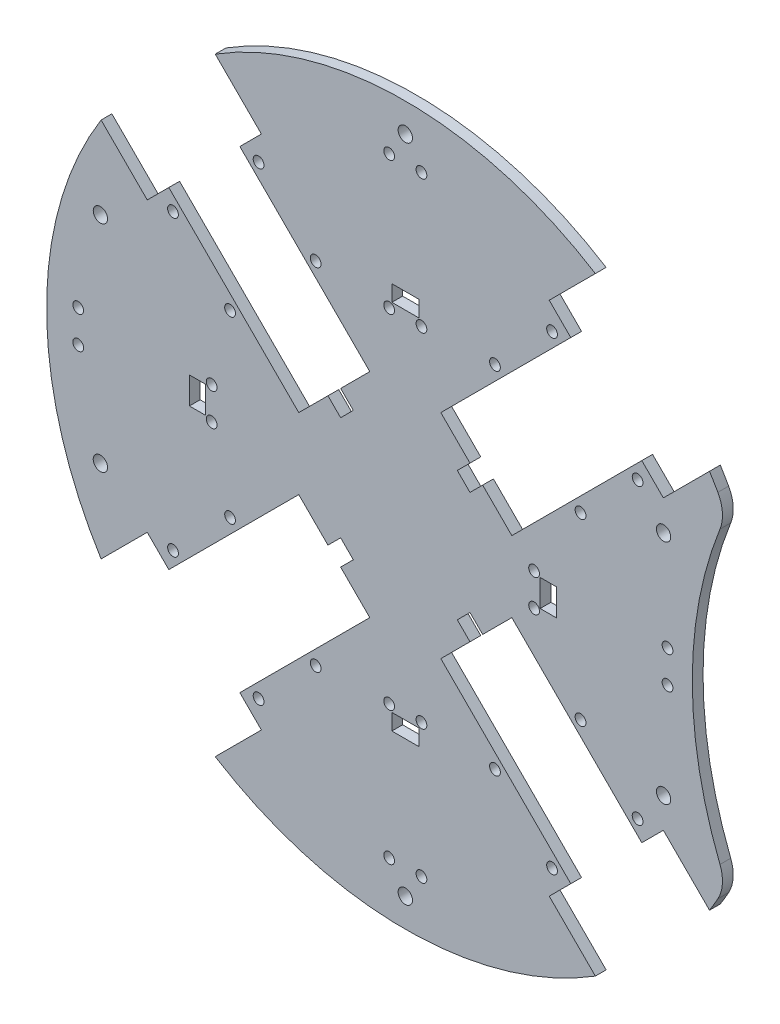
SolidWorks part; units mm, degrees
ref_plane "Alzado" through (0, 0, 0) normal (0, 0, 1) x (1, 0, 0)
ref_plane "Planta" through (0, 0, 0) normal (0, 1, 0) x (1, 0, 0)
ref_plane "Vista lateral" through (0, 0, 0) normal (1, 0, 0) x (0, 0, -1)
sketch "Croquis1" plane through (0, 0, 0) normal (0, 0, 1) x (1, 0, 0)
  circle A0 centre (0, 0) radius 100
  dimension "D1" = 200
extrude "Saliente-Extruir1" add sketch "Croquis1" along normal blind 3
sketch "Croquis3" plane through (0, 0, 3) normal (0, 0, 1) x (1, 0, 0)
  line L0 (0, 0) -> (190, 0) construction
  circle A0 centre (190, 0) radius 110
  dimension "D1" = 220
  dimension "D2" = 190
extrude "Cortar-Extruir1" cut sketch "Croquis3" against normal blind 3
fillet "Redondeo1" radius 10 2 edges at (89.4737, -44.6594, 1.5) (89.4737, 44.6594, 1.5)
sketch "Croquis5" plane through (0, 0, 3) normal (0, 0, 1) x (1, 0, 0)
  line L0 (0, -100) -> (0, 100) construction
  line L1 (-100, 0) -> (80, 0) construction
  line L2 (0, 0) -> (-70.7107, -70.7107) construction
  line L3 (-70.7107, -70.7107) -> (70.7107, 70.7107) construction
  line L4 (0, 0) -> (-70.7107, 70.7107) construction
  line L5 (-70.7107, 70.7107) -> (70.7107, -70.7107) construction
  line L6 (-29.6985, -9.8995) -> (-9.8995, -29.6985)
  line L7 (-29.6985, -9.8995) -> (-84.1457, -64.3467)
  line L8 (-9.8995, -29.6985) -> (-64.3467, -84.1457)
  line L9 (-84.1457, -64.3467) -> (-64.3467, -84.1457)
  line L10 (-9.8995, 29.6985) -> (-29.6985, 9.8995)
  line L11 (-9.8995, 29.6985) -> (-64.3467, 84.1457)
  line L12 (-64.3467, 84.1457) -> (-84.1457, 64.3467)
  line L13 (-29.6985, 9.8995) -> (-84.1457, 64.3467)
  line L14 (29.6985, 9.8995) -> (9.8995, 29.6985)
  line L15 (29.6985, 9.8995) -> (84.1457, 64.3467)
  line L16 (84.1457, 64.3467) -> (64.3467, 84.1457)
  line L17 (9.8995, 29.6985) -> (64.3467, 84.1457)
  line L18 (9.8995, -29.6985) -> (29.6985, -9.8995)
  line L19 (9.8995, -29.6985) -> (64.3467, -84.1457)
  line L20 (64.3467, -84.1457) -> (84.1457, -64.3467)
  line L21 (29.6985, -9.8995) -> (84.1457, -64.3467)
  arc A0 (87.1345, 49.0671) -> (87.1345, -49.0671) centre (0, 0) ccw construction
  arc A1 (87.7193, 40.4803) -> (87.7193, -40.4803) centre (190, 0) ccw construction
  point P36 (0, 0)
  dimension "D1" = 45
  dimension "D2" = 45
  dimension "D3" = 28
  dimension "D4" = 14
  dimension "D5" = 5
  dimension "D6" = 77
  dimension "D8" = 5
  dimension "D9" = 5
  dimension "D7" = 4
extrude "Cortar-Extruir2" cut sketch "Croquis5" against normal blind 10
sketch "Croquis7" plane through (0, 0, 3) normal (0, 0, 1) x (1, 0, 0)
  line L0 (-71.9393, -40.1195) -> (-40.1195, -71.9393)
  line L1 (-71.9393, -40.1195) -> (-88.9099, -57.0901)
  line L2 (-40.1195, -71.9393) -> (-57.0901, -88.9099)
  line L3 (-88.9099, -57.0901) -> (-57.0901, -88.9099)
  line L4 (-29.6985, -9.8995) -> (-79.9138, -60.1148) construction
  line L7 (-73, -73) -> (0, 0) construction
  line L8 (-40.1195, 71.9393) -> (-71.9393, 40.1195)
  line L9 (-40.1195, 71.9393) -> (-57.0901, 88.9099)
  line L10 (-57.0901, 88.9099) -> (-88.9099, 57.0901)
  line L11 (-71.9393, 40.1195) -> (-88.9099, 57.0901)
  line L12 (71.9393, 40.1195) -> (40.1195, 71.9393)
  line L13 (71.9393, 40.1195) -> (88.9099, 57.0901)
  line L14 (88.9099, 57.0901) -> (57.0901, 88.9099)
  line L15 (40.1195, 71.9393) -> (57.0901, 88.9099)
  line L16 (40.1195, -71.9393) -> (71.9393, -40.1195)
  line L17 (40.1195, -71.9393) -> (57.0901, -88.9099)
  line L18 (57.0901, -88.9099) -> (88.9099, -57.0901)
  line L19 (71.9393, -40.1195) -> (88.9099, -57.0901)
  line L23 (-21.5668, -18.0312) -> (-18.0312, -21.5668)
  line L24 (-21.5668, -18.0312) -> (-18.0312, -14.4957)
  line L25 (-18.0312, -21.5668) -> (-14.4957, -18.0312)
  line L26 (-18.0312, -14.4957) -> (-14.4957, -18.0312)
  line L42 (-21.5668, 18.0312) -> (-18.0312, 14.4957)
  line L43 (-18.0312, 21.5668) -> (-14.4957, 18.0312)
  line L44 (-18.0312, 21.5668) -> (-21.5668, 18.0312)
  line L45 (-14.4957, 18.0312) -> (-18.0312, 14.4957)
  line L46 (18.0312, 21.5668) -> (14.4957, 18.0312)
  line L47 (21.5668, 18.0312) -> (18.0312, 14.4957)
  line L48 (21.5668, 18.0312) -> (18.0312, 21.5668)
  line L49 (18.0312, 14.4957) -> (14.4957, 18.0312)
  line L50 (21.5668, -18.0312) -> (18.0312, -14.4957)
  line L51 (18.0312, -21.5668) -> (14.4957, -18.0312)
  line L52 (18.0312, -21.5668) -> (21.5668, -18.0312)
  line L53 (14.4957, -18.0312) -> (18.0312, -14.4957)
  arc A0 (-79.9138, 60.1148) -> (-79.9138, -60.1148) centre (0, 0) ccw construction
  arc A2 (-79.9138, 60.1148) -> (-79.9138, -60.1148) centre (0, 0) ccw construction
  point P24 (0, 0)
  point P47 (0, -3.5355)
  point P48 (0, 0)
  dimension "D1" = 90
  dimension "D2" = 45
  dimension "D3" = 24
  dimension "D4" = 73
  dimension "D5" = 360
  dimension "D6" = 4
  dimension "D7" = 79.2376
  dimension "D8" = 22.5
  dimension "D9" = 5
  dimension "D10" = 2.5
  dimension "D11" = 5
  dimension "D12" = 23
  dimension "D14" = 23
  dimension "D15" = 23
  dimension "D13" = 4
extrude "Cortar-Extruir3" cut sketch "Croquis7" against normal blind 10
sketch "Croquis8" plane through (0, 0, 3) normal (0, 0, 1) x (1, 0, 0)
  line L0 (-71.9393, 40.1195) -> (-65.9289, 46.1299) construction
  line L1 (-65.9289, 46.1299) -> (-29.6985, 9.8995) construction
  line L2 (0, 0) -> (0, 100) construction
  line L3 (-46.1299, 65.9289) -> (-40.1195, 71.9393) construction
  line L4 (52.9877, 84.8075) -> (40.1195, 71.9393) construction
  line L7 (-65.9289, -46.1299) -> (-71.9393, -40.1195) construction
  line L8 (-29.6985, -9.8995) -> (-65.9289, -46.1299) construction
  line L9 (-52.9877, -84.8075) -> (-40.1195, -71.9393) construction
  line L11 (-100, 0) -> (80, 0) construction
  line L14 (71.9393, 40.1195) -> (84.8075, 52.9877) construction
  circle A0 centre (-64.7622, 40.9044) radius 1.5
  circle A1 centre (-48.8523, 24.9945) radius 1.5023
  circle A2 centre (-24.9945, 48.8523) radius 1.5
  circle A3 centre (-40.9044, 64.7622) radius 1.5
  circle A16 centre (64.7622, 40.9044) radius 1.5
  circle A17 centre (48.8523, 24.9945) radius 1.5
  circle A18 centre (24.9945, 48.8523) radius 1.5023
  circle A19 centre (40.9044, 64.7622) radius 1.5
  circle A20 centre (40.9044, -64.7622) radius 1.5
  circle A21 centre (24.9945, -48.8523) radius 1.5
  circle A22 centre (48.8523, -24.9945) radius 1.5023
  circle A23 centre (64.7622, -40.9044) radius 1.5
  circle A24 centre (-64.7622, -40.9044) radius 1.5
  circle A25 centre (-48.8523, -24.9945) radius 1.5
  circle A26 centre (-24.9945, -48.8523) radius 1.5023
  circle A27 centre (-40.9044, -64.7622) radius 1.5
  circle A28 centre (0, 92) radius 2
  arc A29 (52.9877, 84.8075) -> (-52.9877, 84.8075) centre (0, 0) ccw construction
  circle A32 centre (0, -92) radius 2
  arc A35 (-52.9877, -84.8075) -> (52.9877, -84.8075) centre (0, 0) ccw construction
  arc A36 (-84.8075, 52.9877) -> (-84.8075, -52.9877) centre (0, 0) ccw construction
  arc A38 (87.7193, 40.4803) -> (87.7193, -40.4803) centre (190, 0) ccw construction
  circle A44 centre (72, 31.6949) radius 2
  circle A45 centre (72, -31.6949) radius 2
  circle A46 centre (-85, -30) radius 2
  circle A47 centre (-85, 30) radius 2
  point P41 (0, 0)
  dimension "D1" = 3
  dimension "D2" = 22.5
  dimension "D3" = 33.74
  dimension "D4" = 3.0046
  dimension "D5" = 33.74
  dimension "D6" = 27.02
  dimension "D7" = 3
  dimension "D8" = 3
  dimension "D9" = 2.87
  dimension "D10" = 22.5
  dimension "D11" = 2.87
  dimension "D12" = 27.02
  dimension "D14" = 4.52
  dimension "D15" = 2.87
  dimension "D16" = 4
  dimension "D17" = 92
  dimension "D18" = 42.5538
  dimension "D21" = 92
  dimension "D22" = 42.5538
  dimension "D19" = 4
  dimension "D20" = 4
  dimension "D23" = 6
  dimension "D24" = 72
  dimension "D25" = 4
  dimension "D26" = 4
  dimension "D27" = 30
  dimension "D28" = 85
  dimension "D29" = 30
  dimension "D30" = 85
  dimension "D13" = 4
extrude "Cortar-Extruir4" cut sketch "Croquis8" against normal blind 10
sketch "Croquis9" plane through (0, 0, 3) normal (0, 0, 1) x (1, 0, 0)
  line L0 (-100, 0) -> (80, 0) construction
  line L5 (0, -100) -> (0, 100) construction
  line L6 (37.6, 3.75) -> (42.1, 3.75)
  line L7 (37.6, 3.75) -> (37.6, -3.75)
  line L8 (37.6, -3.75) -> (42.1, -3.75)
  line L9 (42.1, 3.75) -> (42.1, -3.75)
  line L10 (-3.75, -49.5) -> (3.75, -49.5)
  line L11 (-55.6901, 3.75) -> (-60.1901, 3.75)
  line L12 (-55.6901, 3.75) -> (-55.6901, -3.75)
  line L13 (-55.6901, -3.75) -> (-60.1901, -3.75)
  line L14 (-60.1901, 3.75) -> (-60.1901, -3.75)
  line L15 (-3.75, 54) -> (3.75, 54)
  line L16 (-3.75, 54) -> (-3.75, 49.5)
  line L17 (-3.75, 49.5) -> (3.75, 49.5)
  line L18 (3.75, 54) -> (3.75, 49.5)
  line L19 (3.75, -54) -> (3.75, -49.5)
  line L20 (-3.75, -54) -> (3.75, -54)
  line L21 (-3.75, -54) -> (-3.75, -49.5)
  circle A0 centre (73.1, -4.5) radius 1.5
  circle A1 centre (35.9, 4.5) radius 1.5
  arc A2 (-84.8075, 52.9877) -> (-84.8075, -52.9877) centre (0, 0) ccw construction
  arc A3 (87.7193, 40.4803) -> (87.7193, -40.4803) centre (190, 0) ccw construction
  circle A4 centre (73.1, 4.5) radius 1.5
  circle A5 centre (35.9, -4.5) radius 1.5
  arc A6 (-52.9877, -84.8075) -> (52.9877, -84.8075) centre (0, 0) ccw construction
  arc A7 (52.9877, 84.8075) -> (-52.9877, 84.8075) centre (0, 0) ccw construction
  circle A8 centre (-91.1901, 4.5) radius 1.5
  circle A9 centre (-91.1901, -4.5) radius 1.5
  circle A10 centre (-53.9901, 4.5) radius 1.5
  circle A11 centre (-53.9901, -4.5) radius 1.5
  circle A12 centre (-4.5, 85) radius 1.5
  circle A13 centre (4.5, 85) radius 1.5
  circle A14 centre (-4.5, 47.8) radius 1.5
  circle A15 centre (4.5, 47.8) radius 1.5
  circle A20 centre (-4.5, -47.8) radius 1.5
  circle A21 centre (4.5, -47.8) radius 1.5
  circle A22 centre (4.5, -85) radius 1.5
  circle A23 centre (-4.5, -85) radius 1.5
  dimension "D6" = 35.9
  dimension "D7" = 3
  dimension "D8" = 37.2
  dimension "D9" = 37.2
  dimension "D10" = 3
  dimension "D11" = 3
  dimension "D12" = 4.5
  dimension "D13" = 4.5
  dimension "D14" = 3
  dimension "D15" = 3
  dimension "D16" = 3
  dimension "D3" = 35.9
  dimension "D21" = 4.5
  dimension "D22" = 4.5
  dimension "D23" = 3
  dimension "D24" = 3
  dimension "D25" = 4.5
  dimension "D26" = 4.5
  dimension "D27" = 37.2
  dimension "D28" = 37.2
  dimension "D29" = 91.1901
  dimension "D30" = 91.1901
  dimension "D35" = 3
  dimension "D36" = 3
  dimension "D37" = 4.5
  dimension "D38" = 4.5
  dimension "D39" = 3
  dimension "D40" = 3
  dimension "D41" = 4.5
  dimension "D42" = 4.5
  dimension "D43" = 37.2
  dimension "D44" = 37.2
  dimension "D45" = 85
  dimension "D46" = 85
  dimension "D51" = 4.5
  dimension "D52" = 4.5
  dimension "D17" = 4.5
  dimension "D18" = 7.5
  dimension "D19" = 1.7
  dimension "D20" = 0.75
  dimension "D31" = 7.5
  dimension "D32" = 4.5
  dimension "D33" = 1.7
  dimension "D34" = 0.75
  dimension "D47" = 7.5
  dimension "D48" = 4.5
  dimension "D49" = 0.75
  dimension "D50" = 1.7
extrude "Cortar-Extruir5" cut sketch "Croquis9" against normal blind 10
